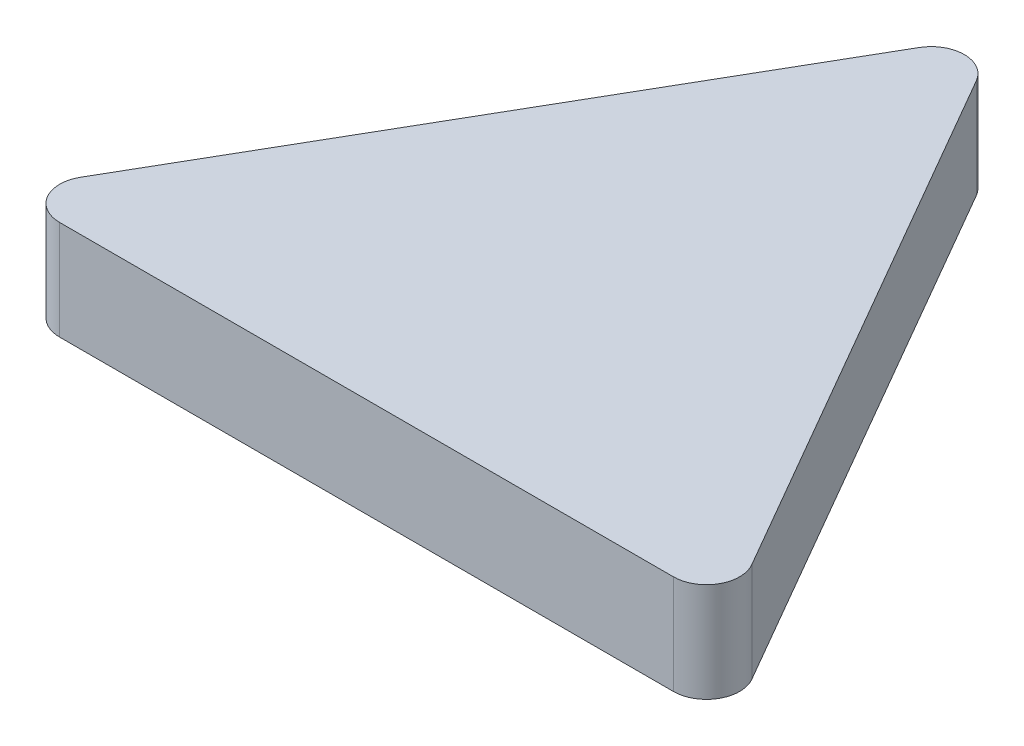
SolidWorks part; units mm, degrees
material "Pine"
ref_plane "Front Plane" through (0, 0, 0) normal (0, 0, 1) x (1, 0, 0)
ref_plane "Top Plane" through (0, 0, 0) normal (0, 1, 0) x (1, 0, 0)
ref_plane "Right Plane" through (0, 0, 0) normal (1, 0, 0) x (0, 0, -1)
sketch "Sketch1" plane through (0, 0, 0) normal (0, 1, 0) x (1, 0, 0)
  line L0 (34.925, 20.164) -> (0, 0) construction
  line L1 (0, 0) -> (0, -40.3279) construction
  line L2 (-5.4993, 71.1308) -> (-64.3507, -30.8029)
  line L5 (-58.8515, -40.3279) -> (58.8515, -40.3279)
  line L8 (64.3507, -30.8029) -> (5.4993, 71.1308)
  line L9 (-34.925, 20.164) -> (0, 0) construction
  arc A3 (5.4993, 71.1308) -> (-5.4993, 71.1308) centre (0, 67.9558) ccw
  arc A4 (-64.3507, -30.8029) -> (-58.8515, -40.3279) centre (-58.8515, -33.9779) ccw
  arc A5 (58.8515, -40.3279) -> (64.3507, -30.8029) centre (58.8515, -33.9779) ccw
  point P4 (0, 0)
  point P7 (0, 0)
  point P15 (-69.85, -40.3279)
  point P18 (69.85, -40.3279)
  dimension "D2" = 6.35
  dimension "D1" = 139.7
extrude "Boss-Extrude1" add sketch "Sketch1" along normal blind 19.05
